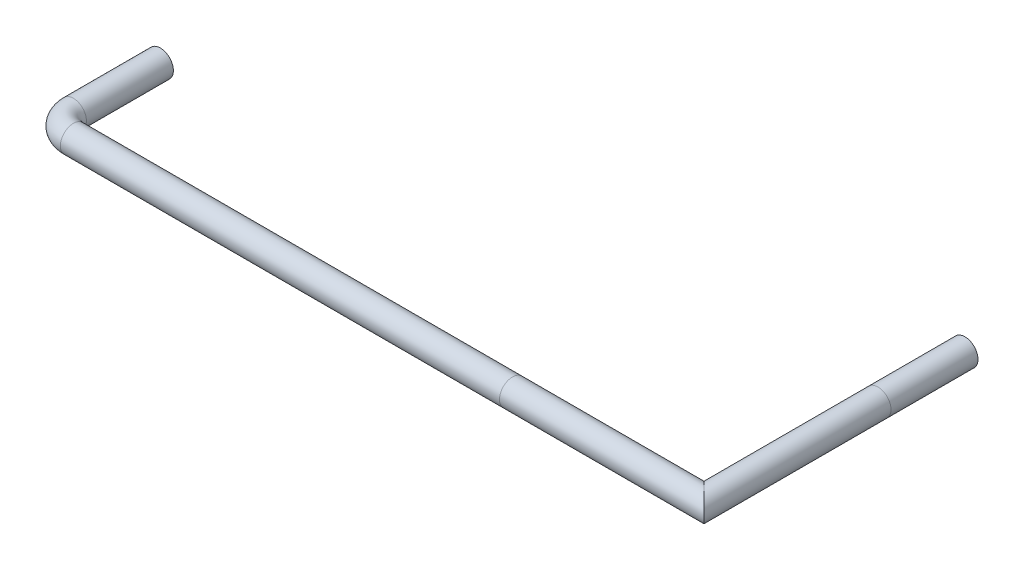
SolidWorks part; units mm, degrees
material "AISI 1020 Steel, Cold Rolled"
ref_plane "Front Plane" through (0, 0, 0) normal (0, 0, 1) x (1, 0, 0)
ref_plane "Top Plane" through (0, 0, 0) normal (0, 1, 0) x (1, 0, 0)
ref_plane "Right Plane" through (0, 0, 0) normal (1, 0, 0) x (0, 0, -1)
sketch "Sketch1" plane through (0, 0, 0) normal (0, 1, 0) x (1, 0, 0)
  line L0 (0, 0) -> (-20.1946, 0)
  line L1 (-21.1946, 1) -> (-21.1946, 5)
  line L2 (8.8054, 8) -> (8.8054, 12)
  line L3 (8.8054, 8) -> (8.8054, 0)
  line L4 (8.8054, 0) -> (0, 0)
  arc A1 (-20.1946, 0) -> (-21.1946, 1) centre (-20.1946, 1) cw
  dimension "D1" = 7
  dimension "D2" = 30
  dimension "D3" = 5
  dimension "D4" = 12
  dimension "D5" = 8.8054
  dimension "D6" = 4
ref_plane "Plane1" through (8.8054, 0, -12) normal (0, 0, 1) x (1, 0, 0)
sketch "Sketch2" plane through (8.8054, 0, -12) normal (0, 0, 1) x (1, 0, 0)
  line L0 (0, 0) -> (-8.8054, 0) construction
  circle A0 centre (0, 0) radius 0.6
  dimension "D1" = 1.2
sweep "Sweep2" add profiles "Sketch2" path "Sketch1"
